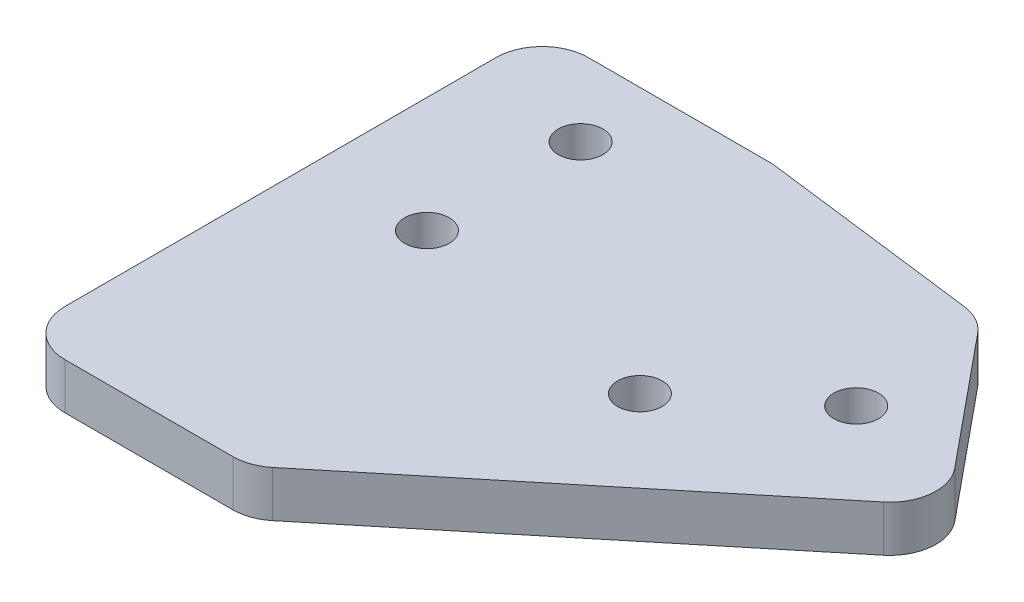
SolidWorks part; units mm, degrees
material "Thornel Mat VMA"
ref_plane "前视基准面" through (0, 0, 0) normal (0, 0, 1) x (1, 0, 0)
ref_plane "上视基准面" through (0, 0, 0) normal (0, 1, 0) x (1, 0, 0)
ref_plane "右视基准面" through (0, 0, 0) normal (1, 0, 0) x (0, 0, -1)
other "Configuration Table"
sketch "草图1" plane through (0, 0, 0) normal (0, 1, 0) x (1, 0, 0)
  line L0 (-15, 150) -> (-185, 10.3576) construction
  line L1 (-185, -150) -> (185, -150) construction
  line L2 (-185, -150) -> (-185, 150) construction
  line L3 (-185, 150) -> (185, 150) construction
  line L4 (185, -150) -> (185, 150) construction
  line L5 (-185, -150) -> (185, 150) construction
  line L6 (-185, 150) -> (185, -150) construction
  line L7 (-15, 150) -> (-5.4789, 138.4091) construction
  line L8 (-185, 10.3576) -> (-175.4789, -1.2333) construction
  line L9 (-5.4789, 138.4091) -> (-175.4789, -1.2333) construction
  line L10 (0, 196.6631) -> (0, -186.1301) construction
  line L11 (185, 10.3576) -> (175.4789, -1.2333) construction
  line L12 (15, 150) -> (5.4789, 138.4091) construction
  line L13 (5.4789, 138.4091) -> (175.4789, -1.2333) construction
  line L14 (15, 150) -> (185, 10.3576) construction
  line L15 (185, 150) -> (200, 150) construction
  line L16 (-185, 150) -> (185, 150) construction
  line L17 (-185, 150) -> (-185, 165) construction
  line L18 (-185, 165) -> (185, 165) construction
  line L19 (185, 150) -> (185, 165) construction
  line L20 (-185, 150) -> (-200, 150) construction
  line L21 (-185, 150) -> (-185, -150) construction
  line L22 (-185, -150) -> (-200, -150) construction
  line L23 (-200, 150) -> (-200, -150) construction
  line L24 (185, -150) -> (200, -150) construction
  line L25 (200, 150) -> (200, -150) construction
  line L26 (-200, -33) -> (-185, -33) construction
  line L32 (-192.5, 71.2471) -> (-192.5, -68.4689) construction
  line L33 (-146.0358, 32.6579) -> (-223.6914, -31.1304) construction
  line L34 (-200, 25) -> (-185, 25)
  line L35 (-185, 25) -> (-169.5455, 23.0524)
  line L36 (-169.5455, 23.0524) -> (-160.0244, 11.4615)
  line L37 (-160.0244, 11.4615) -> (-175.4789, -1.2333)
  line L39 (-200, -4.9173) -> (-200, 25)
  line L40 (-175.4789, -1.2333) -> (-185, -9.0542)
  line L41 (-185, -9.0542) -> (-200, -9.0542)
  line L42 (-200, -9.0542) -> (-200, -4.9173)
  circle A0 centre (-176.3758, 7.7358) radius 1.45
  circle A1 centre (-168.6486, 14.0832) radius 1.45
  circle A2 centre (-192.5, 20) radius 1.45
  circle A3 centre (-192.5, 10) radius 1.45
  point P0 (0, 0)
  dimension "D11" = 5
  dimension "D12" = 10
  dimension "D13" = 5
  dimension "D14" = 5
  dimension "D15" = 130
  dimension "D16" = 10
  dimension "D17" = 2.9
  dimension "D1" = 370
  dimension "D2" = 300
  dimension "D3" = 220
  dimension "D4" = 15
  dimension "D5" = 15
  dimension "D6" = 183
  dimension "D7" = 170
  dimension "D8" = 15
  dimension "D9" = 7.5
  dimension "D10" = 7.5
extrude "凸台-拉伸1" add sketch "草图1" along normal blind 3
fillet "圆角1" radius 3 6 edges at (-185, 1.5, 9.0542) (-200, 1.5, 9.0542) (-200, 1.5, -25) (-185, 1.5, -25) (-169.5455, 1.5, -23.0524) (-160.0244, 1.5, -11.4615)
